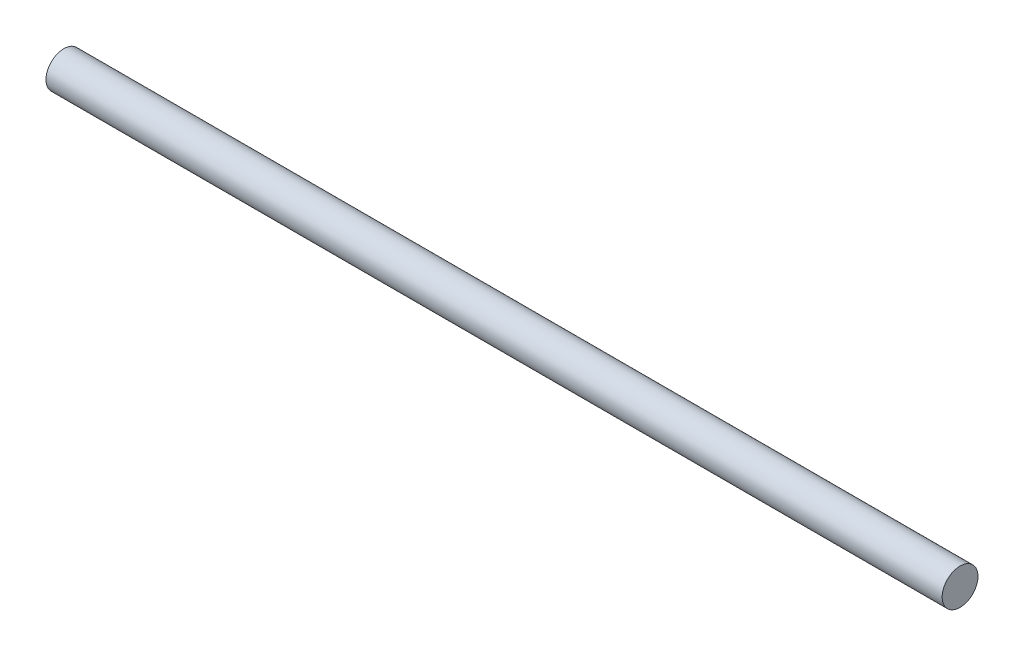
SolidWorks part; units mm, degrees
material "AISI 316 退火不锈钢条 (SS)"
ref_plane "前视基准面" through (0, 0, 0) normal (0, 0, 1) x (1, 0, 0)
ref_plane "上视基准面" through (0, 0, 0) normal (0, 1, 0) x (1, 0, 0)
ref_plane "右视基准面" through (0, 0, 0) normal (1, 0, 0) x (0, 0, -1)
sketch "草图1" plane through (0, 0, 0) normal (1, 0, 0) x (0, 0, -1)
  circle A0 centre (0, 0) radius 2
  dimension "D1" = 4
extrude "凸台-拉伸1" add sketch "草图1" along normal blind 100
